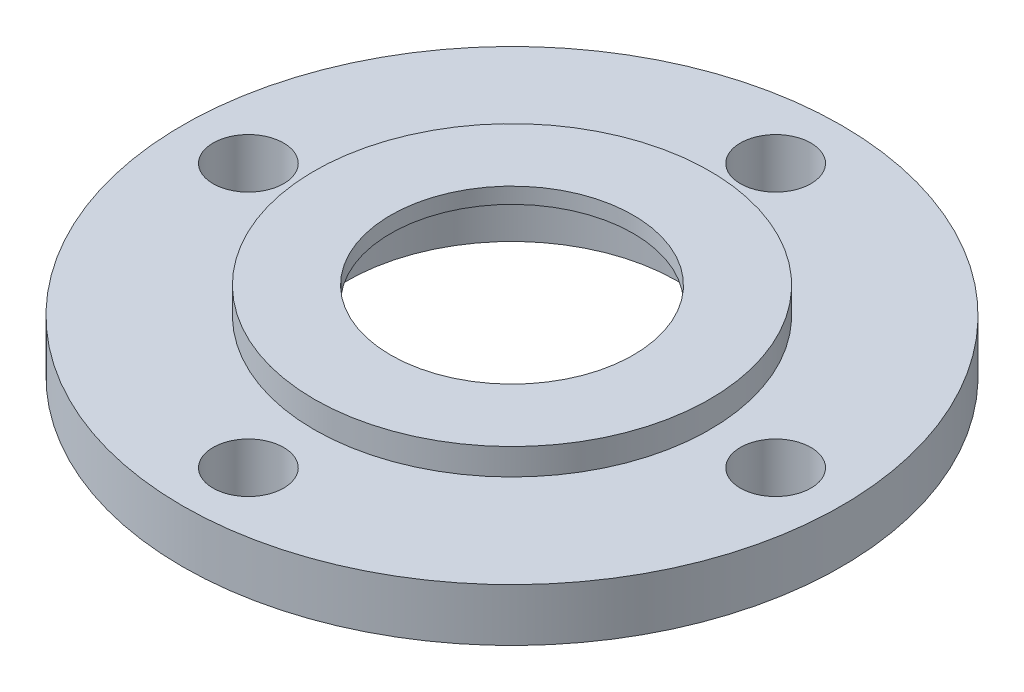
SolidWorks part; units mm, degrees
ref_plane "Front Plane" through (0, 0, 0) normal (0, 0, 1) x (1, 0, 0)
ref_plane "Top Plane" through (0, 0, 0) normal (0, 1, 0) x (1, 0, 0)
ref_plane "Right Plane" through (0, 0, 0) normal (1, 0, 0) x (0, 0, -1)
sketch "Sketch1" plane through (0, 0, 0) normal (0, 1, 0) x (1, 0, 0)
  circle A0 centre (0, 0) radius 15.875
  dimension "D1" = 31.75
extrude "Boss-Extrude1" add sketch "Sketch1" along normal blind 2.54
sketch "Sketch2" plane through (0, 2.54, 0) normal (0, 1, 0) x (1, 0, 0)
  circle A0 centre (0, 0) radius 9.525
  dimension "D1" = 19.05
extrude "Boss-Extrude2" add sketch "Sketch2" along normal blind 1.27
sketch "Sketch3" plane through (0, 0, 0) normal (0, -1, 0) x (1, 0, 0)
  circle A0 centre (0, 0) radius 7.9629
  dimension "D1" = 15.9258
extrude "Cut-Extrude1" cut sketch "Sketch3" against normal blind 3.048
sketch "Sketch4" plane through (0, 3.81, 0) normal (0, 1, 0) x (1, 0, 0)
  circle A0 centre (0, 0) radius 5.842
  dimension "D1" = 11.684
extrude "Cut-Extrude2" cut sketch "Sketch4" against normal up to next
sketch "Sketch5" plane through (0, 2.54, 0) normal (0, 1, 0) x (1, 0, 0)
  line L0 (0, 15.875) -> (0, 0) construction
  circle A0 centre (0, 12.7) radius 1.7
  circle A1 centre (0, 0) radius 15.875 construction
  circle A2 centre (12.7, 0) radius 1.7
  circle A3 centre (0, -12.7) radius 1.7
  circle A4 centre (-12.7, 0) radius 1.7
  point P18 (0, 0)
  dimension "D2" = 3.4
  dimension "D1" = 12.7
  dimension "D3" = 4
extrude "Cut-Extrude3" cut sketch "Sketch5" against normal up to next
